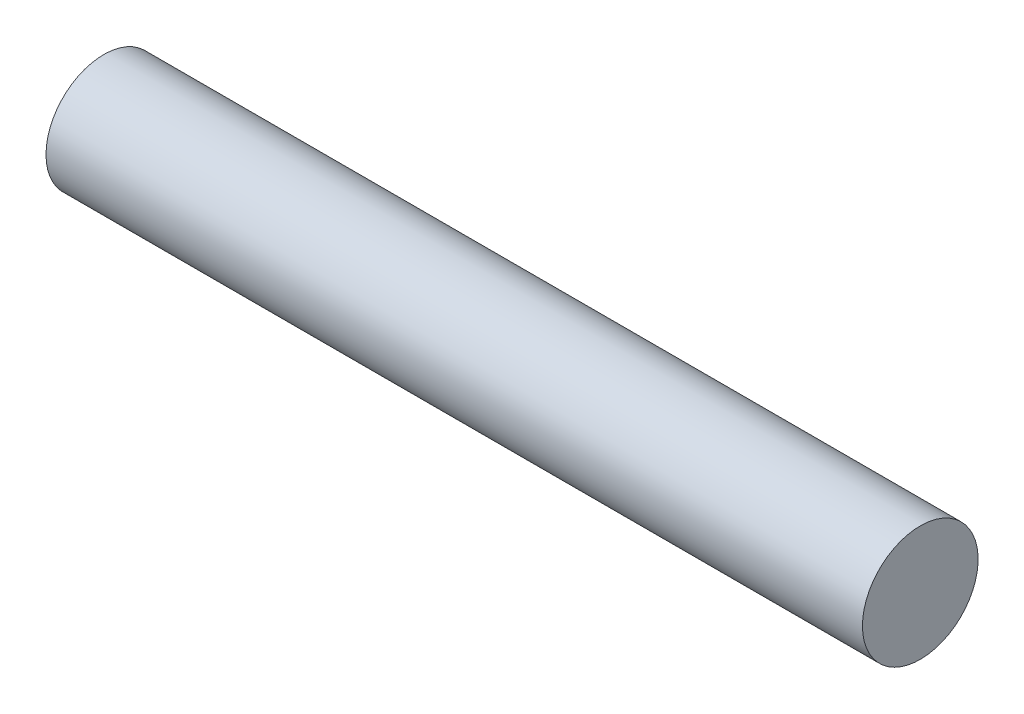
SolidWorks part; units mm, degrees
ref_plane "Plan de face" through (0, 0, 0) normal (0, 0, 1) x (1, 0, 0)
ref_plane "Plan de dessus" through (0, 0, 0) normal (0, 1, 0) x (1, 0, 0)
ref_plane "Plan de droite" through (0, 0, 0) normal (1, 0, 0) x (0, 0, -1)
sketch "Esquisse1" plane through (0, 0, 0) normal (0, 0, 1) x (1, 0, 0)
  line L0 (0, 0) -> (240, 0)
  line L1 (240, 0) -> (240, 17)
  line L2 (240, 17) -> (0, 17)
  line L3 (0, 17) -> (0, 0)
  point P5 (120, 0)
  dimension "D1" = 17
  dimension "D2" = 240
revolve "Révolution1" add sketch "Esquisse1" angle 360 about L0
